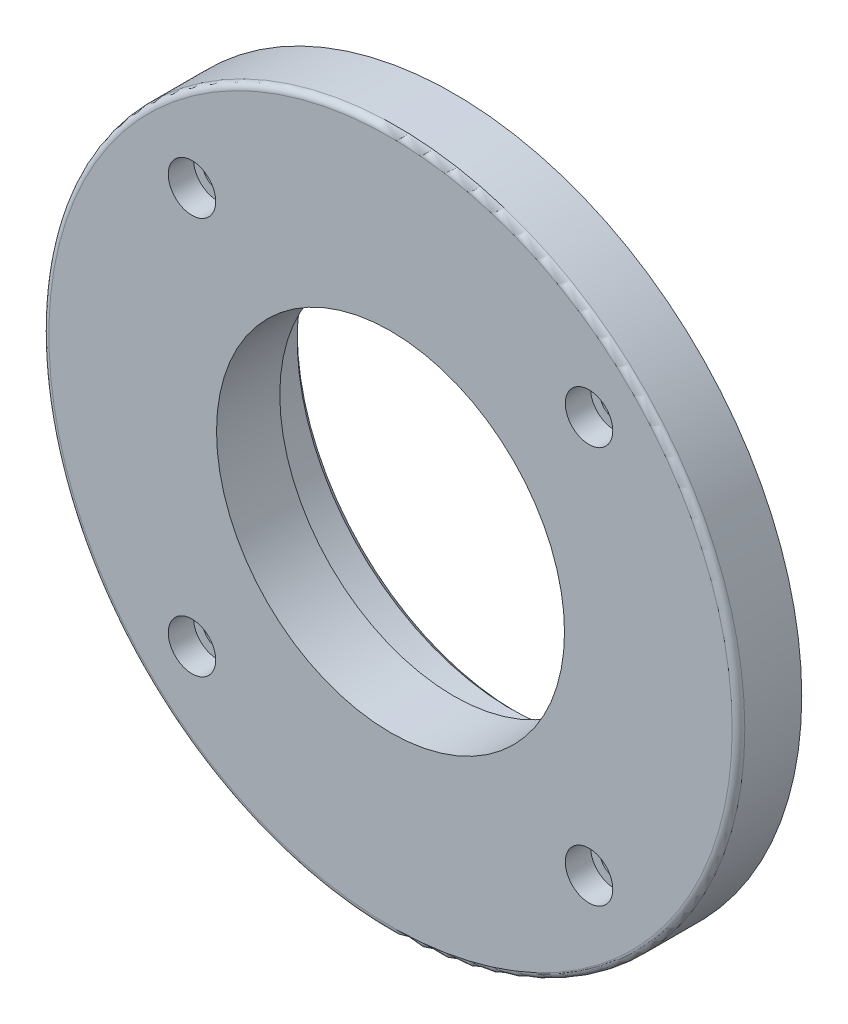
SolidWorks part; units mm, degrees
ref_plane "Piano frontale" through (0, 0, 0) normal (0, 0, 1) x (1, 0, 0)
ref_plane "Piano superiore" through (0, 0, 0) normal (0, 1, 0) x (1, 0, 0)
ref_plane "Piano destro" through (0, 0, 0) normal (1, 0, 0) x (0, 0, -1)
sketch "Schizzo1" plane through (0, 0, 0) normal (0, 0, 1) x (1, 0, 0)
  line L0 (0, 76.5777) -> (0, 0) construction
  line L1 (-69.6481, 0) -> (61.5529, 0) construction
  circle A0 centre (0, 0) radius 110
  circle A4 centre (0, 0) radius 55
  point P25 (0, 0)
  dimension "D1" = 220
  dimension "D5" = 110
extrude "Estrusione-Estrusione1" add sketch "Schizzo1" along normal blind 20
sketch "Schizzo2" plane through (0, 0, 0) normal (1, 0, 0) x (0, 0, -1)
  line L0 (0, 0) -> (56.1057, 0) construction
  line L1 (0, 78.75) -> (20, 78.75)
  line L3 (20, 78.75) -> (20, 67.5)
  line L4 (20, 67.5) -> (0, 67.5)
  line L5 (0, 67.5) -> (0, 78.75)
  dimension "D1" = 135
  dimension "D2" = 157.5
  dimension "D3" = 20
revolve "Rivoluzione1" add sketch "Schizzo2" angle 360 about L0
fillet "Raccordo1" radius 2 1 edges at (110, 0, 20)
chamfer "Smusso1" distance 2 angle 45 1 edges at (67.5, 0, -20)
sketch "Schizzo3" plane through (0, 0, 20) normal (0, 0, 1) x (1, 0, 0)
  line L0 (0, 112.0062) -> (0, -151.4596) construction
  line L1 (0, 0) -> (-18.408, 18.408) construction
  line L2 (-47.7297, 47.7297) -> (-77.7817, 77.7817) construction
  circle A0 centre (0, 0) radius 110 construction
  circle A4 centre (0, 0) radius 67.5 construction
  point P11 (-62.7557, 62.7557)
  dimension "D1" = 45
hole_wizard "Foro lamato per Vite M8 a testa cilindrica piana-1" positions "Schizzo5" profile "Schizzo4" counterbore size "M8" standard "ISO" end condition through all
sketch "Schizzo5" plane through (0, 0, 20) normal (0, 0, 1) x (1, 0, 0)
  point P0 (-62.7557, 62.7557)
sketch "Schizzo4" plane through (-62.7557, 62.7557, 20) normal (1, 0, 0) x (0, -1, 0)
  line L0 (0, 0) -> (0, 40)
  line L1 (0, 40) -> (4.5, 40)
  line L3 (4.5, 40) -> (4.5, 8)
  line L4 (4.5, 8) -> (7.5, 8)
  line L5 (7.5, 8) -> (7.5, 0)
  line L7 (7.5, 0) -> (0, 0)
  line L11 (0, -6.35) -> (0, 107.95) construction
  dimension "Thru Hole Dia." = 9
  dimension "Thru Hole Depth" = 40
  dimension "C'Bore Dia." = 15
  dimension "C'Bore Depth" = 8
pattern_circular "RipetizioneCircolare1" count 4 over 360 about axis through (0, 0, 0) along (0, 0, 1) of "Foro lamato per Vite M8 a testa cilindrica piana-1"
